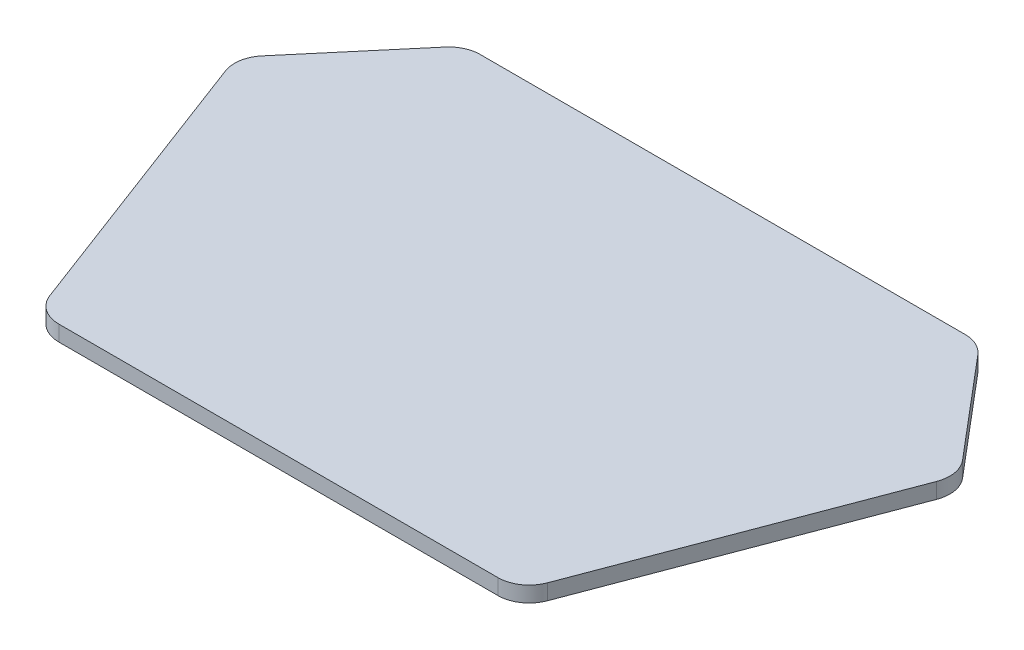
SolidWorks part; units mm, degrees
ref_plane "Front Plane" through (0, 0, 0) normal (0, 0, 1) x (1, 0, 0)
ref_plane "Top Plane" through (0, 0, 0) normal (0, 1, 0) x (1, 0, 0)
ref_plane "Right Plane" through (0, 0, 0) normal (1, 0, 0) x (0, 0, -1)
sketch "Sketch1" plane through (0, 0, 0) normal (0, 1, 0) x (1, 0, 0)
  line L0 (-35.5875, 37.7559) -> (35.5875, 37.7559)
  line L1 (52.1771, 17.0021) -> (36.4976, -24.4614)
  line L2 (-32.2212, -27.4163) -> (32.2212, -27.4163)
  line L4 (39.079, 36.1356) -> (51.3921, 21.571)
  line L5 (-52.1771, 17.0021) -> (-36.4976, -24.4614)
  line L6 (-39.079, 36.1356) -> (-51.3921, 21.571)
  arc A0 (-35.5875, 37.7559) -> (-39.079, 36.1356) centre (-35.5875, 33.1839) ccw
  arc A1 (36.4976, -24.4614) -> (32.2212, -27.4163) centre (32.2212, -22.8443) cw
  arc A2 (-36.4976, -24.4614) -> (-32.2212, -27.4163) centre (-32.2212, -22.8443) ccw
  arc A3 (39.079, 36.1356) -> (35.5875, 37.7559) centre (35.5875, 33.1839) ccw
  arc A4 (52.1771, 17.0021) -> (51.3921, 21.571) centre (47.9006, 18.6192) ccw
  arc A5 (-52.1771, 17.0021) -> (-51.3921, 21.571) centre (-47.9006, 18.6192) cw
  point P8 (-37.7092, 37.7559)
  point P17 (37.7092, 37.7559)
  point P18 (0, 37.7559)
  point P22 (53.1282, 19.5174)
  point P25 (-53.1282, 19.5174)
  point P26 (0, 7.947)
  dimension "D2" = 4.572
extrude "Extrude1" add sketch "Sketch1" against normal blind 2.286
sketch "Sketch4" plane through (0, 0, 0) normal (0, 1, 0) x (1, 0, 0)
  arc A0 (-26.9439, 20.8344) -> (26.9439, 20.8344) centre (0, -12.1097) cw
  arc A1 (-26.9439, 20.8344) -> (-26.9439, -4.9404) centre (2.1448, 7.947) ccw
  arc A2 (-26.9439, -4.9404) -> (26.9439, -4.9404) centre (0, 26.7561) ccw
  arc A3 (26.9439, -4.9404) -> (26.9439, 20.8344) centre (-0.5519, 7.947) ccw
